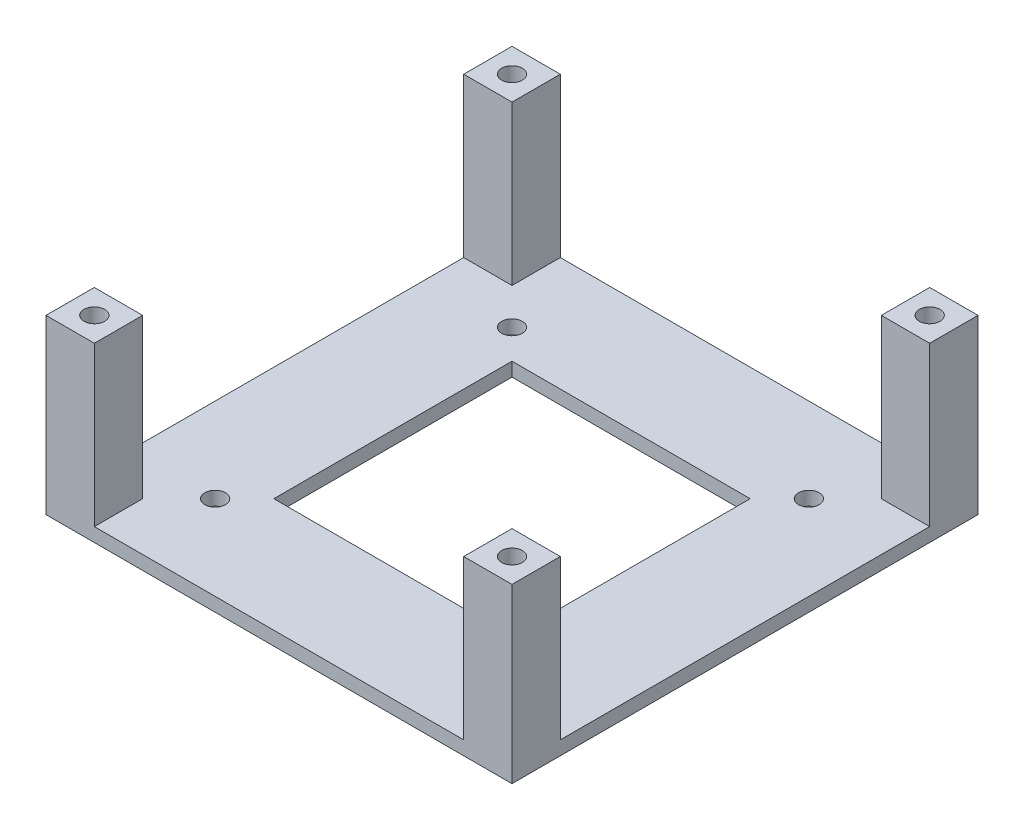
SolidWorks part; units mm, degrees
ref_plane "Front Plane" through (0, 0, 0) normal (0, 0, 1) x (1, 0, 0)
ref_plane "Top Plane" through (0, 0, 0) normal (0, 1, 0) x (1, 0, 0)
ref_plane "Right Plane" through (0, 0, 0) normal (1, 0, 0) x (0, 0, -1)
sketch "Sketch1" plane through (0, 0, 0) normal (0, 1, 0) x (1, 0, 0)
  line L0 (0, 27.75) -> (0, -27.75) construction
  line L1 (-27.75, -27.75) -> (27.75, -27.75)
  line L2 (-27.75, -27.75) -> (-27.75, 27.75)
  line L3 (-27.75, 27.75) -> (27.75, 27.75)
  line L4 (27.75, -27.75) -> (27.75, 27.75)
  line L5 (-27.75, -27.75) -> (27.75, 27.75) construction
  line L6 (-27.75, 27.75) -> (27.75, -27.75) construction
  line L11 (-18.6731, -18.6731) -> (18.6731, 18.6731) construction
  line L12 (-13.6731, 13.6731) -> (23.6731, -23.6731) construction
  line L13 (-15.25, -15.25) -> (15.25, -15.25)
  line L14 (-15.25, -15.25) -> (-15.25, 15.25)
  line L15 (-15.25, 15.25) -> (15.25, 15.25)
  line L16 (15.25, -15.25) -> (15.25, 15.25)
  line L17 (-17.25, -17.25) -> (17.25, -17.25)
  line L18 (-17.25, -17.25) -> (-17.25, 17.25)
  line L19 (-17.25, 17.25) -> (17.25, 17.25)
  line L20 (17.25, -17.25) -> (17.25, 17.25)
  line L21 (-17.25, -17.25) -> (17.25, 17.25) construction
  line L22 (-17.25, 17.25) -> (17.25, -17.25) construction
  line L23 (-27.75, 0) -> (27.75, 0) construction
  circle A0 centre (-21.5, -21.5) radius 1.5
  circle A1 centre (21.5, -21.5) radius 1.5
  circle A2 centre (21.5, 21.5) radius 1.5
  circle A3 centre (-21.5, 21.5) radius 1.5
  point P0 (0, 0)
  point P5 (0, 0)
  point P15 (0, 0)
  dimension "D6" = 43
  dimension "D7" = 3
  dimension "D1" = 55.5
  dimension "D2" = 55.5
  dimension "D3" = 12.5
  dimension "D4" = 12.5
  dimension "D5" = 2
extrude "Boss-Extrude2" add sketch "Sketch1" along normal blind 2 contours L1 L4 L3 L2 A1 A0 L20 L17 L18 L19 A2 A3
sketch "Sketch2" plane through (0, 0, 0) normal (0, 1, 0) x (1, 0, 0)
  line L1 (33.75, -33.75) -> (-33.75, -33.75)
  line L2 (33.75, -33.75) -> (33.75, 33.75)
  line L3 (33.75, 33.75) -> (-33.75, 33.75)
  line L4 (-33.75, -33.75) -> (-33.75, 33.75)
  line L5 (33.75, -33.75) -> (-33.75, 33.75) construction
  line L6 (33.75, 33.75) -> (-33.75, -33.75) construction
  line L7 (-33.75, 0) -> (33.75, 0) construction
  line L12 (-27.75, -27.75) -> (27.75, -27.75)
  line L13 (-27.75, -27.75) -> (-27.75, 27.75)
  line L14 (-27.75, 27.75) -> (27.75, 27.75)
  line L15 (27.75, -27.75) -> (27.75, 27.75)
  line L16 (-27.75, -27.75) -> (27.75, 27.75) construction
  line L17 (-27.75, 27.75) -> (27.75, -27.75) construction
  line L18 (0, 33.75) -> (0, -33.75) construction
  circle A0 centre (-30.25, 30.25) radius 1.5
  circle A1 centre (30.25, 30.25) radius 1.5
  circle A2 centre (30.25, -30.25) radius 1.5
  circle A3 centre (-30.25, -30.25) radius 1.5
  point P0 (0, 0)
  point P8 (0, 0)
  point P9 (0, 0)
  dimension "D3" = 3
  dimension "D4" = 2
  dimension "D1" = 67.5
  dimension "D2" = 67.5
extrude "Boss-Extrude5" add sketch "Sketch2" along normal blind 2
sketch "Sketch3" plane through (0, 0, 0) normal (0, 1, 0) x (1, 0, 0)
  line L1 (-33.75, -33.75) -> (33.75, -33.75)
  line L2 (-33.75, -33.75) -> (-33.75, 33.75)
  line L3 (-33.75, 33.75) -> (33.75, 33.75)
  line L4 (33.75, -33.75) -> (33.75, 33.75)
  line L5 (-33.75, -33.75) -> (33.75, 33.75) construction
  line L6 (-33.75, 33.75) -> (33.75, -33.75) construction
  line L11 (-27.75, -27.75) -> (27.75, 27.75) construction
  line L12 (-27.75, 27.75) -> (27.75, -27.75) construction
  line L19 (0, 33.75) -> (0, -33.75) construction
  line L21 (-26.75, 26.75) -> (-33.75, 26.75)
  line L22 (-26.75, 26.75) -> (-26.75, 33.75)
  line L23 (-33.75, 0) -> (33.75, 0) construction
  line L28 (-26.75, 33.75) -> (-33.75, 33.75)
  line L29 (-33.75, 26.75) -> (-33.75, 33.75)
  line L31 (-26.75, 26.75) -> (-33.75, 33.75) construction
  line L35 (-33.75, 26.75) -> (-33.75, -26.75)
  line L38 (-26.75, -33.75) -> (26.75, -33.75)
  line L43 (33.75, 26.75) -> (33.75, -26.75)
  line L46 (26.75, 33.75) -> (-26.75, 33.75)
  line L48 (-26.75, 33.75) -> (-33.75, 26.75) construction
  line L49 (26.75, 26.75) -> (33.75, 26.75)
  line L50 (26.75, 26.75) -> (26.75, 33.75)
  line L51 (26.75, 33.75) -> (33.75, 33.75)
  line L52 (33.75, 26.75) -> (33.75, 33.75)
  line L53 (26.75, 26.75) -> (33.75, 33.75) construction
  line L54 (26.75, 33.75) -> (33.75, 26.75) construction
  line L55 (26.75, -26.75) -> (33.75, -26.75)
  line L56 (26.75, -26.75) -> (26.75, -33.75)
  line L57 (26.75, -33.75) -> (33.75, -33.75)
  line L58 (33.75, -26.75) -> (33.75, -33.75)
  line L59 (26.75, -26.75) -> (33.75, -33.75) construction
  line L60 (26.75, -33.75) -> (33.75, -26.75) construction
  line L61 (-26.75, -26.75) -> (-33.75, -26.75)
  line L62 (-26.75, -26.75) -> (-26.75, -33.75)
  line L63 (-26.75, -33.75) -> (-33.75, -33.75)
  line L64 (-33.75, -26.75) -> (-33.75, -33.75)
  line L65 (-26.75, -26.75) -> (-33.75, -33.75) construction
  line L66 (-26.75, -33.75) -> (-33.75, -26.75) construction
  circle A3 centre (30.25, 30.25) radius 1.5
  circle A4 centre (-30.25, 30.25) radius 1.5
  circle A5 centre (-30.25, -30.25) radius 1.5
  circle A6 centre (30.25, -30.25) radius 1.5
  point P0 (0, 0)
  point P5 (0, 0)
extrude "Boss-Extrude6" add sketch "Sketch3" along normal blind 25
